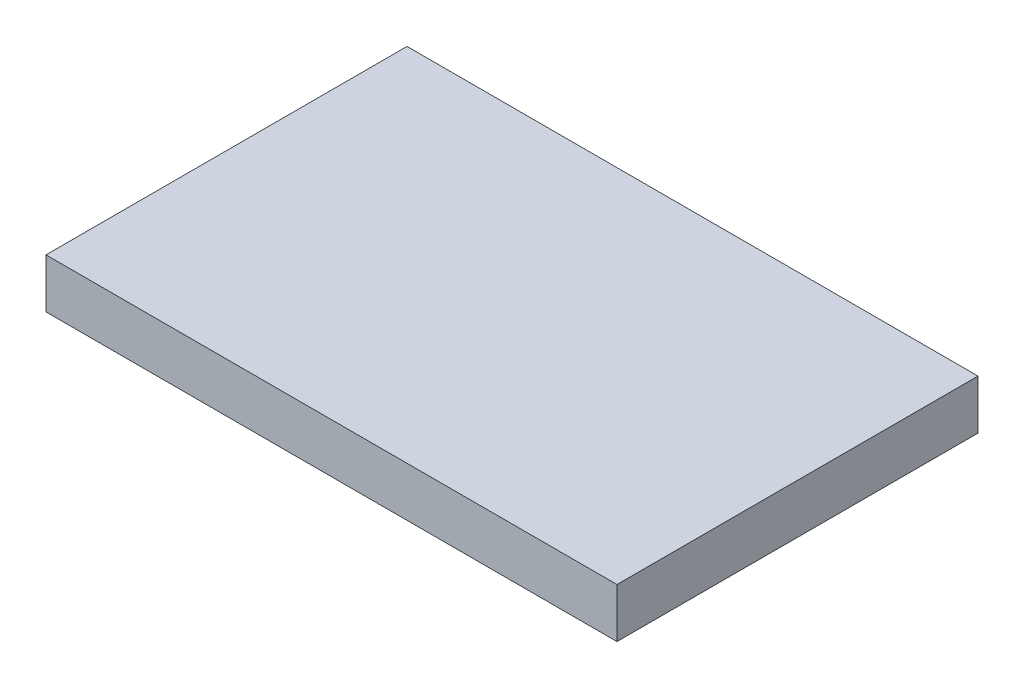
SolidWorks part; units mm, degrees
ref_plane "Front Plane" through (0, 0, 0) normal (0, 0, 1) x (1, 0, 0)
ref_plane "Top Plane" through (0, 0, 0) normal (0, 1, 0) x (1, 0, 0)
ref_plane "Right Plane" through (0, 0, 0) normal (1, 0, 0) x (0, 0, -1)
sketch "Sketch1" plane through (0, 0, 0) normal (0, 1, 0) x (1, 0, 0)
  line L1 (0, 0) -> (115.5197, 0)
  line L2 (0, 0) -> (0, 73.041)
  line L3 (0, 73.041) -> (115.5197, 73.041)
  line L4 (115.5197, 0) -> (115.5197, 73.041)
extrude "Boss-Extrude2" add sketch "Sketch1" along normal blind 10
